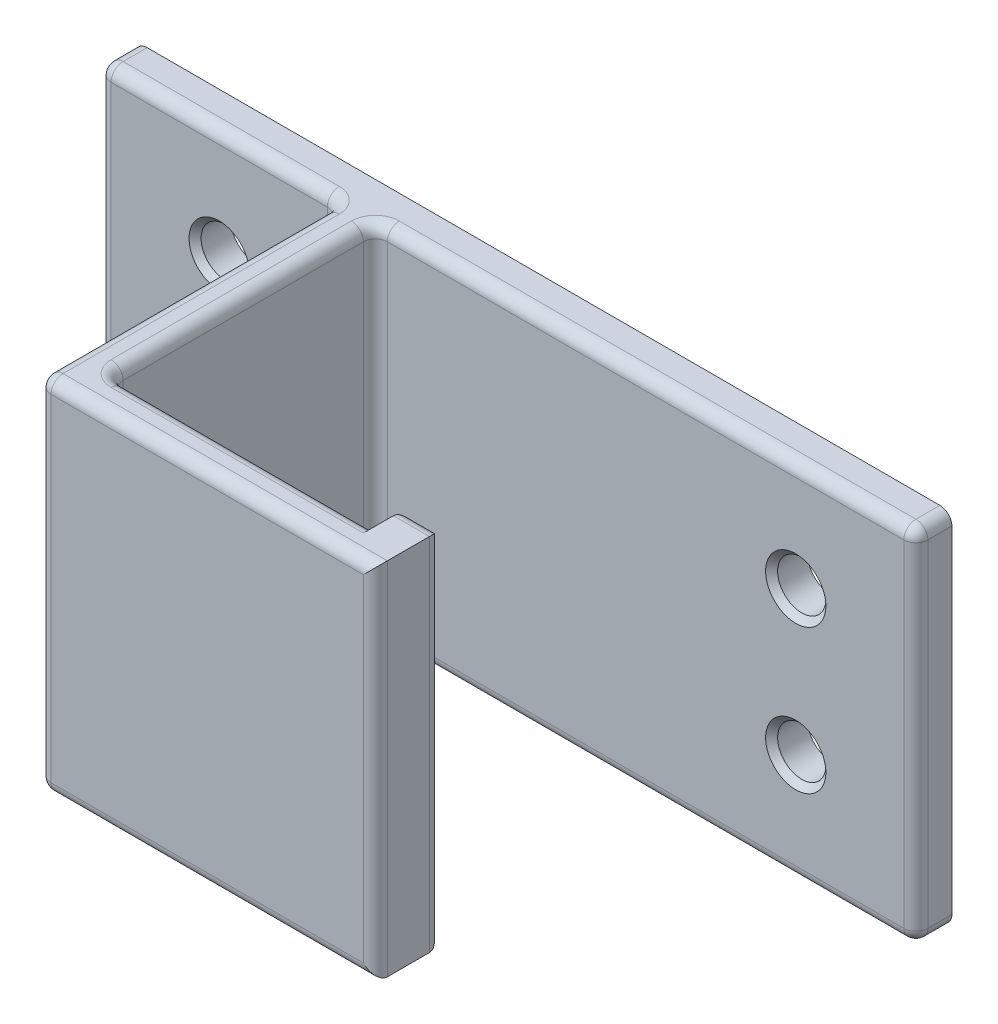
SolidWorks part; units mm, degrees
ref_plane "Front Plane" through (0, 0, 0) normal (0, 0, 1) x (1, 0, 0)
ref_plane "Top Plane" through (0, 0, 0) normal (0, 1, 0) x (1, 0, 0)
ref_plane "Right Plane" through (0, 0, 0) normal (1, 0, 0) x (0, 0, -1)
sketch "Sketch1" plane through (0, 0, 0) normal (0, 0, 1) x (1, 0, 0)
  line L1 (0, 0) -> (-86.36, 0)
  line L2 (0, 0) -> (0, 38.1)
  line L3 (0, 38.1) -> (-86.36, 38.1)
  line L4 (-86.36, 0) -> (-86.36, 38.1)
  dimension "D1" = 38.1
  dimension "D2" = 86.36
extrude "Boss-Extrude1" add sketch "Sketch1" along normal blind 3.81
sketch "Sketch2" plane through (0, 0, 3.81) normal (0, 0, 1) x (1, 0, 0)
  line L0 (-86.36, 0) -> (0, 0) construction
  line L1 (-57.15, 0) -> (-60.96, 0)
  line L2 (-57.15, 0) -> (-57.15, 38.1)
  line L3 (-57.15, 38.1) -> (-60.96, 38.1)
  line L4 (-60.96, 0) -> (-60.96, 38.1)
  line L5 (0, 38.1) -> (-86.36, 38.1) construction
  line L6 (-86.36, 38.1) -> (-86.36, 0) construction
  point P15 (57.4239, -11.9981)
  dimension "D1" = 3.81
  dimension "D2" = 25.4
extrude "Boss-Extrude2" add sketch "Sketch2" along normal blind 31.75
sketch "Sketch3" plane through (-57.15, 0, 0) normal (1, 0, 0) x (0, 0, -1)
  line L0 (-35.56, 0) -> (-3.81, 0) construction
  line L1 (-35.56, 38.1) -> (-31.75, 38.1)
  line L2 (-35.56, 38.1) -> (-35.56, 0)
  line L3 (-35.56, 0) -> (-31.75, 0)
  line L4 (-31.75, 38.1) -> (-31.75, 0)
  dimension "D1" = 3.81
extrude "Boss-Extrude3" add sketch "Sketch3" along normal blind 31.75
sketch "Sketch4" plane through (0, 0, 31.75) normal (0, 0, -1) x (-1, 0, 0)
  line L0 (25.4, 0) -> (57.15, 0) construction
  line L1 (25.4, 38.1) -> (29.21, 38.1)
  line L2 (25.4, 38.1) -> (25.4, 0)
  line L3 (25.4, 0) -> (29.21, 0)
  line L4 (29.21, 38.1) -> (29.21, 0)
  dimension "D1" = 3.81
extrude "Boss-Extrude4" add sketch "Sketch4" along normal blind 3.175
fillet "Fillet1" radius 1.27 27 edges at (-57.15, 19.05, 31.75) (0, 19.05, 3.81) (-57.15, 19.05, 3.81) (-86.36, 19.05, 3.81) (-60.96, 19.05, 3.81) (-60.96, 19.05, 35.56) (-25.4, 19.05, 35.56) (-86.36, 0, 1.905) (-73.66, 0, 3.81) (-60.96, 0, 19.685) (-43.18, 0, 35.56) (-43.18, 0, 31.75) (-57.15, 0, 17.78) (-28.575, 0, 3.81) (0, 0, 1.905) (0, 38.1, 1.905) (-28.575, 38.1, 3.81) (-57.15, 38.1, 17.78) (-43.18, 38.1, 31.75) (-43.18, 38.1, 35.56) (-60.96, 38.1, 19.685) (-73.66, 38.1, 3.81) (-86.36, 38.1, 1.905) (-27.305, 38.1, 28.575) (-29.21, 19.05, 28.575) (-27.305, 0, 28.575) (-25.4, 19.05, 28.575)
hole_wizard "#10 Clearance Hole1" positions "Sketch5" profile "Sketch7" hole size "#10" standard "ANSI Inch"
sketch "Sketch5" plane through (0, 0, 3.81) normal (0, 0, 1) x (1, 0, 0)
  line L0 (-85.09, 1.27) -> (-62.23, 1.27) construction
  line L1 (-85.09, 36.83) -> (-85.09, 1.27) construction
  line L2 (-62.23, 36.83) -> (-85.09, 36.83) construction
  line L3 (-1.27, 1.27) -> (-1.27, 36.83) construction
  point P0 (-73.66, 11.43)
  point P2 (-73.66, 26.67)
  point P14 (-12.7, 11.43)
  point P16 (-12.7, 26.67)
  point P35 (0, 0)
  point P36 (0, 0)
  point P37 (0, 0)
  point P38 (-12.7, 9.7367)
  point P39 (-12.7, 9.7367)
  dimension "D1" = 10.16
  dimension "D2" = 11.43
  dimension "D3" = 10.16
  dimension "D4" = 11.43
sketch "Sketch7" plane through (-73.66, 11.43, 3.81) normal (1, 0, 0) x (0, -1, 0)
  line L0 (0, 0) -> (0, 5.3428)
  line L1 (0, 5.3428) -> (2.5527, 3.809)
  line L2 (2.5527, 3.809) -> (2.5527, 0.635)
  line L3 (2.5527, 0.635) -> (3.1877, 0)
  line L5 (3.1877, 0) -> (0, 0)
  line L6 (-2.5527, 0.635) -> (-3.1877, 0) construction
  line L10 (0, 5.3428) -> (-2.5527, 3.809) construction
  line L11 (0, -6.35) -> (0, 107.95) construction
  dimension "Hole Dia." = 5.1054
  dimension "Hole Depth" = 3.809
  dimension "Near C'Sink Dia." = 6.3754
  dimension "Near C'Sink Angle" = 90
  dimension "Drill Angle" = 118
